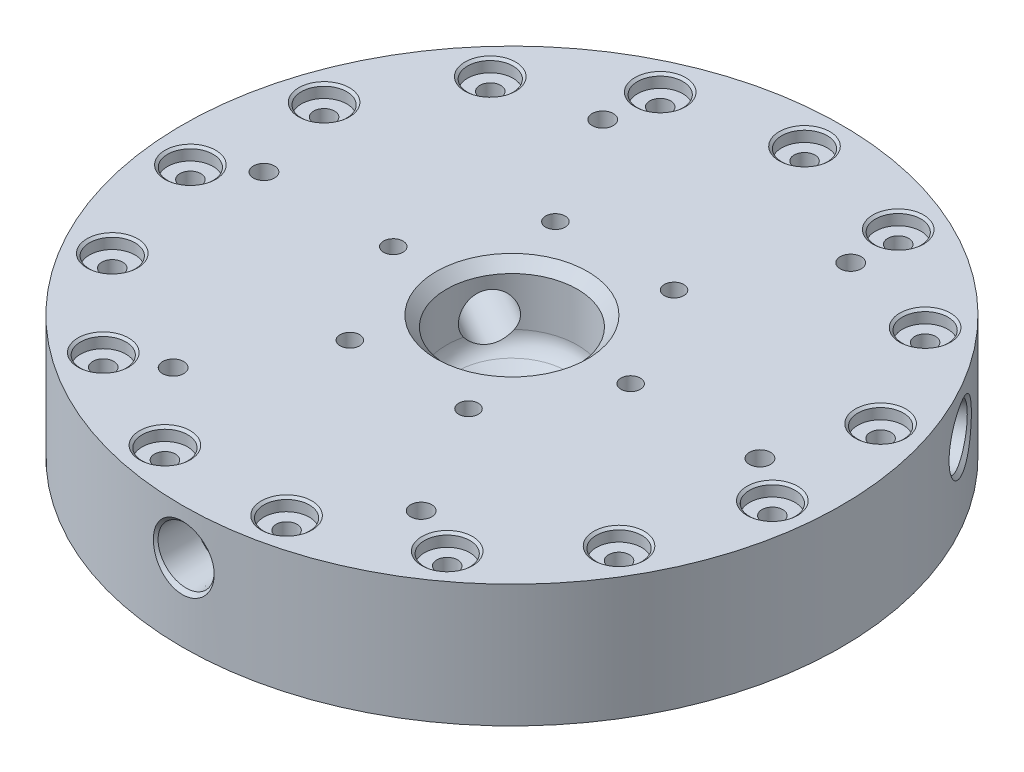
SolidWorks part; units mm, degrees
ref_plane "Front Plane" through (0, 0, 0) normal (0, 0, 1) x (1, 0, 0)
ref_plane "Top Plane" through (0, 0, 0) normal (0, 1, 0) x (1, 0, 0)
ref_plane "Right Plane" through (0, 0, 0) normal (1, 0, 0) x (0, 0, -1)
sketch "Sketch1" plane through (0, 0, 0) normal (0, 1, 0) x (1, 0, 0)
  circle A0 centre (0, 0) radius 80.54
  dimension "D1" = 161.08
extrude "Boss-Extrude1" add sketch "Sketch1" along normal blind 30
sketch "Sketch2" plane through (0, 0, 0) normal (0, 0, 1) x (1, 0, 0)
  line L0 (-5.9533, 0) -> (-5.9533, 4.1132)
  line L1 (-8.4533, 8.4434) -> (-13.5, 11.3571)
  line L2 (-16, 15.6872) -> (-16, 30)
  line L3 (80.54, 30) -> (-80.54, 30) construction
  line L4 (-16, 30) -> (0, 30)
  line L5 (0, 30) -> (0, 0)
  line L6 (0, 0) -> (-5.9533, 0)
  line L7 (-80.54, 0) -> (80.54, 0) construction
  arc A0 (-13.5, 11.3571) -> (-16, 15.6872) centre (-11, 15.6872) cw
  arc A1 (-5.9533, 4.1132) -> (-8.4533, 8.4434) centre (-10.9533, 4.1132) ccw
  point P15 (-5.9533, 7)
  dimension "D5" = 5
  dimension "D1" = 5.9533
  dimension "D2" = 7
  dimension "D3" = 16
  dimension "D4" = 30
revolve "Cut-Revolve1" cut sketch "Sketch2" angle 360 about L5
ref_plane "Plane1" through (0, 0, 80.54) normal (0, 0, 1) x (1, 0, 0)
hole_wizard "1/4 NPT Tapped Hole1" positions "Sketch4" profile "Sketch5" size "1/4" standard "ANSI Inch"
sketch "Sketch4" plane through (0, 0, 80.54) normal (0, 0, 1) x (1, 0, 0)
  point P0 (0, 18.9048)
sketch "Sketch5" plane through (0, 18.9048, 80.54) normal (1, 0, 0) x (0, -1, 0)
  line L0 (0, 0) -> (0, 83.8823)
  line L1 (5.5626, 80.54) -> (0, 83.8823)
  line L2 (-5.5626, 80.54) -> (0, 83.8823) construction
  line L3 (5.5626, 80.54) -> (5.5626, 10.02)
  line L4 (5.5626, 10.02) -> (6.5855, 10.02)
  line L5 (6.5855, 10.02) -> (6.858, 0.9208)
  line L6 (6.858, 0.9208) -> (7.7788, 0)
  line L7 (7.7788, 0) -> (0, 0)
  line L8 (0, -6.35) -> (0, 107.95) construction
  line L9 (-6.858, 0.9208) -> (-7.7788, 0) construction
  line L11 (-5.5626, 10.02) -> (-6.5855, 10.02) construction
  line L12 (-6.5855, 10.02) -> (-6.858, 0.9208) construction
  dimension "Tap Drill Dia." = 11.1252
  dimension "Tap Drill Depth" = 80.54
  dimension "Thread Dia." = 13.716
  dimension "Thread Angle" = 3.43
  dimension "Thread Depth" = 10.02
  dimension "C'Sink Dia." = 15.5575
  dimension "C'Sink Angle" = 90
  dimension "Drill Angle" = 118
pattern_circular "CirPattern1" count 3 over 360 about axis through (0, 0, 0) along (0, 1, 0) of "1/4 NPT Tapped Hole1"
hole_wizard "CBORE for #10 Binding Head Machine Screw1" positions "Sketch6" profile "Sketch7" counterbore size "#10" standard "ANSI Inch" end condition through all
sketch "Sketch6" plane through (0, 30, 0) normal (0, 1, 0) x (1, 0, 0)
  point P0 (0, 71.5)
  dimension "D1" = 71.5
sketch "Sketch7" plane through (0, 30, -71.5) normal (1, 0, 0) x (0, 0, 1)
  line L0 (0, 0) -> (0, 30)
  line L1 (0, 30) -> (2.5527, 30)
  line L3 (2.5527, 30) -> (2.5527, 3.1242)
  line L4 (5.5562, 3.1242) -> (2.5527, 3.1242)
  line L5 (5.5562, 3.1242) -> (5.5562, 0.5328)
  line L6 (5.5562, 0.5328) -> (6.1913, 0)
  line L7 (6.1913, 0) -> (0, 0)
  line L8 (-5.5562, 0.5328) -> (-6.1913, 0) construction
  line L11 (0, -6.35) -> (0, 107.95) construction
  dimension "Thru Hole Dia." = 5.1054
  dimension "Thru Hole Depth" = 30
  dimension "C'Bore Dia." = 11.1125
  dimension "C'Bore Depth" = 3.1242
  dimension "Near C'Sink Dia." = 12.3825
  dimension "Near C'Sink Angle" = 100
pattern_circular "CirPattern2" count 15 over 360 about axis through (0, 0, 0) along (0, 1, 0) of "CBORE for #10 Binding Head Machine Screw1"
sketch "Sketch12" plane through (0, 30, 0) normal (0, 1, 0) x (1, 0, 0)
  line L0 (0, 0) -> (0, 60.61)
  line L1 (0, 0) -> (30.305, 52.4898)
  circle A0 centre (0, 0) radius 60.61
  dimension "D1" = 121.22
  dimension "D2" = 30
hole_wizard "13/64 (0.20313) Diameter Hole3" positions "Sketch17" profile "Sketch19" hole size "13/64" standard "ANSI Inch"
sketch "Sketch17" plane through (0, 30, 0) normal (0, 1, 0) x (1, 0, 0)
  point P0 (30.305, 52.4898)
sketch "Sketch19" plane through (30.305, 30, -52.4898) normal (1, 0, 0) x (0, 0, 1)
  line L0 (0, 0) -> (0, 14.2501)
  line L1 (0, 14.2501) -> (2.5798, 12.7)
  line L2 (2.5798, 12.7) -> (2.5798, 0)
  line L5 (2.5798, 0) -> (0, 0)
  line L10 (0, 14.2501) -> (-2.5798, 12.7) construction
  line L11 (0, -6.35) -> (0, 107.95) construction
  dimension "Hole Dia." = 5.1595
  dimension "Hole Depth" = 12.7
  dimension "Drill Angle" = 118
pattern_circular "CirPattern3" count 6 over 360 about axis through (0, 0, 0) along (0, 1, 0) of "13/64 (0.20313) Diameter Hole3"
sketch "Sketch20" plane through (0, 0, 0) normal (0, -1, 0) x (-1, 0, 0)
  circle A0 centre (0, 0) radius 55.14
  dimension "D1" = 110.28
sketch "Sketch21" plane through (0, 0, 0) normal (0, 0, 1) x (1, 0, 0)
  line L0 (-80.54, 0) -> (80.54, 0) construction
  line L1 (60, 0) -> (65, 0)
  line L2 (60, 0) -> (60, 3)
  line L3 (60, 3) -> (65, 3)
  line L4 (65, 0) -> (65, 3)
  line L5 (0, 0) -> (0, -8.9782) construction
  dimension "D1" = 60
  dimension "D2" = 5
  dimension "D3" = 3
revolve "Cut-Revolve2" cut sketch "Sketch21" angle 360 about L5
chamfer "Chamfer1" distance 2.5 angle 45 1 edges at (-16, 30, 0)
hole_wizard "3/16 (0.1875) Diameter Hole1" positions "Sketch27" profile "Sketch28" hole size "3/16" standard "ANSI Inch"
sketch "Sketch27" plane through (0, 30, 0) normal (0, 1, 0) x (1, 0, 0)
  point P0 (29, 0)
  dimension "D1" = 29
sketch "Sketch28" plane through (29, 30, 0) normal (1, 0, 0) x (0, 0, 1)
  line L0 (0, 0) -> (0, 13.4308)
  line L1 (0, 13.4308) -> (2.3812, 12)
  line L2 (2.3812, 12) -> (2.3812, 0)
  line L5 (2.3812, 0) -> (0, 0)
  line L10 (0, 13.4308) -> (-2.3813, 12) construction
  line L11 (0, -6.35) -> (0, 107.95) construction
  dimension "Hole Dia." = 4.7625
  dimension "Hole Depth" = 12
  dimension "Drill Angle" = 118
pattern_circular "CirPattern4" count 6 over 360 about axis through (0, 0, 0) along (0, 1, 0) of "3/16 (0.1875) Diameter Hole1"
